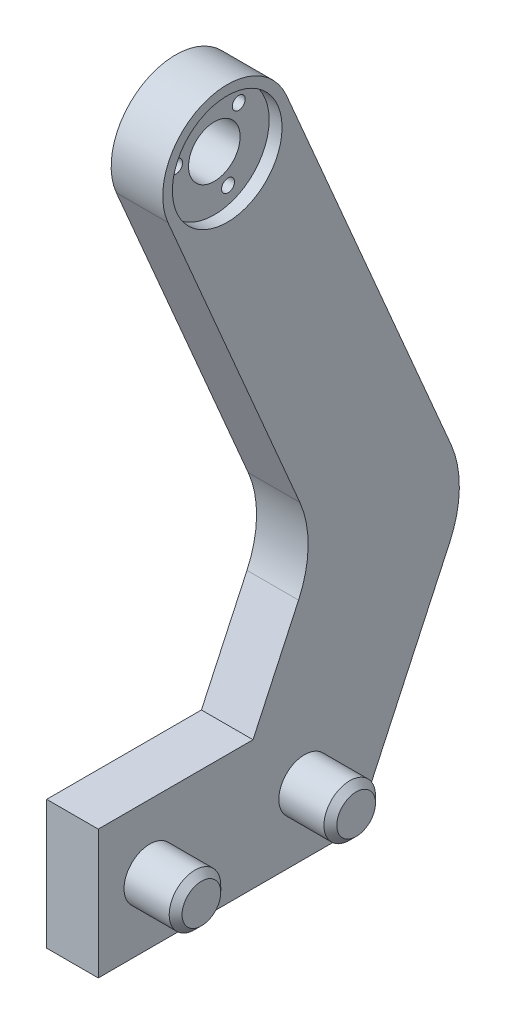
SolidWorks part; units mm, degrees
material "ABS"
ref_plane "Front Plane" through (0, 0, 0) normal (0, 0, 1) x (1, 0, 0)
ref_plane "Top Plane" through (0, 0, 0) normal (0, 1, 0) x (1, 0, 0)
ref_plane "Right Plane" through (0, 0, 0) normal (1, 0, 0) x (0, 0, -1)
sketch "Sketch1" plane through (0, 0, 0) normal (0, 0, 1) x (1, 0, 0)
  line L0 (0, 0) -> (0, -174.625)
  line L1 (0, -174.625) -> (171.45, -174.625)
  line L2 (171.45, -174.625) -> (171.45, 0)
  line L3 (171.45, 0) -> (158.75, 0)
  line L4 (158.75, 0) -> (158.75, -142.875)
  line L5 (158.75, -142.875) -> (12.7, -142.875)
  line L6 (12.7, -142.875) -> (12.7, 0)
  line L7 (12.7, 0) -> (0, 0)
  dimension "D1" = 171.45
  dimension "D2" = 12.7
  dimension "D3" = 31.75
  dimension "D4" = 174.625
extrude "Boss-Extrude1" add sketch "Sketch1" along normal blind 88.9
sketch "Sketch2" plane through (0, -142.875, 0) normal (0, 1, 0) x (1, 0, 0)
  line L0 (158.75, -88.9) -> (158.75, 0) construction
  line L1 (12.7, 0) -> (158.75, 0)
  line L2 (12.7, 0) -> (12.7, -25.4)
  line L3 (12.7, -25.4) -> (158.75, -25.4)
  line L4 (158.75, 0) -> (158.75, -25.4)
  line L5 (158.75, -88.9) -> (12.7, -88.9) construction
  line L6 (0, -50.8) -> (71.8503, -85.7079)
  line L9 (85.725, 0) -> (85.725, -57.15) construction
  line L10 (171.45, -50.8) -> (99.5997, -85.7079)
  line L12 (0, -50.8) -> (171.45, -50.8) construction
  line L13 (171.45, -50.8) -> (171.45, -88.9)
  line L14 (171.45, -88.9) -> (0, -88.9)
  line L15 (0, -88.9) -> (0, -50.8)
  circle A0 centre (85.725, -57.15) radius 31.75
  line M10 (158.75, 0) -> (12.7, 0)
  line M11 (12.7, 0) -> (12.7, -88.9)
  line M13 (158.75, -88.9) -> (158.75, 0)
  dimension "D3" = 63.5
  dimension "D1" = 63.5
  dimension "D2" = 38.1
extrude "Cut-Extrude2" cut sketch "Sketch2" against normal through all both and the other way through all contours L3 M11 M13 M10
sketch "Sketch3" plane through (0, -174.625, 0) normal (0, -1, 0) x (1, 0, 0)
  circle A2 centre (85.725, 57.15) radius 28.575
  dimension "D1" = 57.15
extrude "Cut-Extrude5" cut sketch "Sketch3" against normal offset from surface (28.575 mm away) 3.175 up to face at (85.725, -142.875, 57.15)
sketch "Sketch4" plane through (0, -146.05, 0) normal (0, -1, 0) x (1, 0, 0)
  circle A0 centre (85.725, 57.15) radius 28.575 construction
  circle A1 centre (85.725, 57.15) radius 28.575 construction
  circle A2 centre (85.725, 57.15) radius 12.7
  dimension "D1" = 25.4
extrude "Cut-Extrude6" cut sketch "Sketch4" against normal through all both and the other way through all
sketch "Sketch5" plane through (171.45, 0, 0) normal (1, 0, 0) x (0, 0, -1)
  line L0 (-88.9, 0) -> (0, 0) construction
  line L1 (-44.45, -142.875) -> (-69.85, -142.875) construction
  line L2 (-44.45, -142.875) -> (-69.85, -142.875) construction
  line L3 (-57.15, -142.875) -> (-57.15, 0) construction
  line L4 (-71.7453, -22.1194) -> (-39.2695, -98.0259)
  line L5 (-42.5547, -9.6306) -> (-2.0475, -104.3089)
  line L6 (-50.8, -142.875) -> (-39.5832, -118.7117)
  line L8 (-88.9, -174.625) -> (-88.9, 0) construction
  line L9 (-25.4, -174.625) -> (-2.3613, -124.9947)
  line L11 (-50.8, -142.875) -> (-88.9, -142.875)
  line L12 (0, -174.625) -> (0, 0) construction
  line L13 (-88.9, -174.625) -> (0, -174.625) construction
  line L14 (-25.4, -174.625) -> (0, -174.625)
  line L15 (0, -174.625) -> (0, 0)
  line L16 (0, 0) -> (-88.9, 0)
  line L17 (-88.9, 0) -> (-88.9, -142.875)
  line L18 (-25.4, -174.625) -> (-25.4, -142.875) construction
  line L19 (-25.4, -174.625) -> (-25.4, -142.875) construction
  circle A0 centre (-57.15, -15.875) radius 15.875
  arc A3 (-2.3613, -124.9947) -> (-2.0475, -104.3089) centre (-25.4, -114.3) ccw
  arc A5 (-39.5832, -118.7117) -> (-39.2695, -98.0259) centre (-62.622, -108.017) ccw
  dimension "D1" = 31.75
  dimension "D2" = 25.4
  dimension "D4" = 25.4
  dimension "D5" = 34.858
  dimension "D3" = 60.325
  dimension "D6" = 38.1
extrude "Cut-Extrude7" cut sketch "Sketch5" against normal through all both and the other way through all
sketch "Sketch6" plane through (171.45, 0, 0) normal (1, 0, 0) x (0, 0, -1)
  circle A0 centre (-57.15, -15.875) radius 9.525
  arc A1 (-42.5547, -9.6306) -> (-71.7453, -22.1194) centre (-57.15, -15.875) ccw construction
  dimension "D1" = 6.35
extrude "Cut-Extrude8" cut sketch "Sketch6" against normal up to surface (12.7 mm away) and the other way through all up to face at (158.75, -102.6264, 33.4448)
sketch "Sketch7" plane through (12.7, 0, 0) normal (1, 0, 0) x (0, 0, -1)
  circle A0 centre (-57.15, -15.875) radius 9.525 construction
  circle A1 centre (-57.15, -15.875) radius 9.525 construction
  circle A2 centre (-57.15, -15.875) radius 6.35
  dimension "D1" = 12.7
extrude "Cut-Extrude9" cut sketch "Sketch7" against normal up to surface (12.7 mm away) up to face at (0, -109.8263, 45.3403)
sketch "Sketch12" plane through (12.7, 0, 0) normal (1, 0, 0) x (0, 0, -1)
  circle A0 centre (-57.15, -15.875) radius 13.5
  dimension "D1" = 27
extrude "Cut-Extrude13" cut sketch "Sketch12" against normal blind 3.175
sketch "Sketch14" plane through (12.7, 0, 0) normal (1, 0, 0) x (0, 0, -1)
  circle A0 centre (-53.7708, -24.7804) radius 1.5875
  circle A1 centre (-66.5519, -14.3488) radius 1.5875
  circle A2 centre (-51.1273, -8.4958) radius 1.5875
extrude "Cut-Extrude14" cut sketch "Sketch14" against normal through all both and the other way through all
sketch "Sketch15" plane through (0, 0, 88.9) normal (0, 0, 1) x (1, 0, 0)
  line L0 (12.7, -98.0259) -> (12.7, -22.1194) construction
  line L1 (12.7, -174.625) -> (171.45, -174.625)
  line L2 (12.7, -174.625) -> (12.7, 0)
  line L3 (12.7, 0) -> (171.45, 0)
  line L4 (171.45, -174.625) -> (171.45, 0)
  line L5 (171.45, -22.1194) -> (171.45, -98.0259) construction
  line L6 (0, -174.625) -> (171.45, -174.625) construction
  line L7 (171.45, 0) -> (158.75, 0) construction
extrude "Cut-Extrude15" cut sketch "Sketch15" against normal through all both and the other way through all
sketch "Sketch16" plane through (12.7, 0, 0) normal (1, 0, 0) x (0, 0, -1)
  line L0 (-88.9, -142.875) -> (-88.9, -174.625) construction
  line L1 (-25.4, -174.625) -> (-88.9, -174.625) construction
  circle A0 centre (-76.2, -158.75) radius 6.35
  circle A1 centre (-38.1, -158.75) radius 6.35
  dimension "D1" = 38.1
  dimension "D3" = 12.7
  dimension "D2" = 12.7
  dimension "D4" = 15.875
extrude "Boss-Extrude2" add sketch "Sketch16" along normal blind 12.7
chamfer "Chamfer1" distance 1.5875 angle 45 2 edges at (25.4, -158.75, 31.75) (25.4, -158.75, 69.85)
